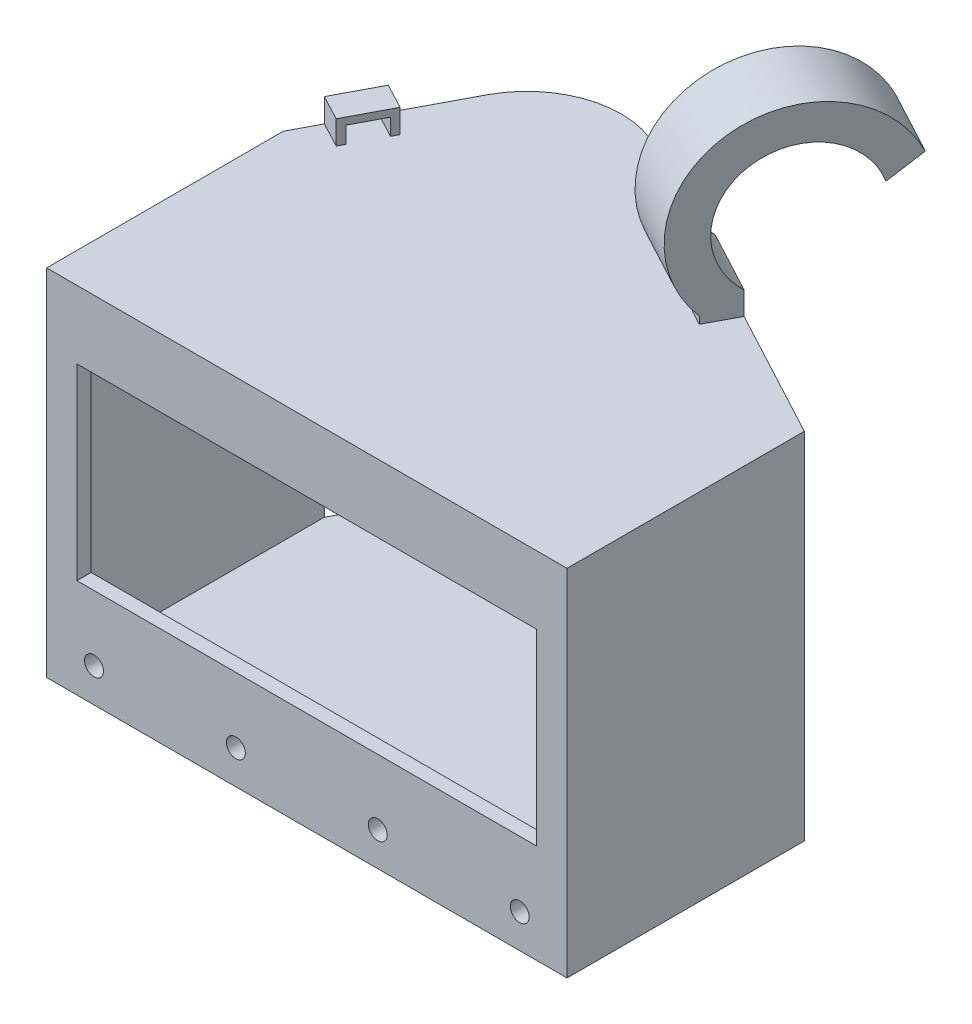
SolidWorks part; units mm, degrees
ref_plane "Plano frontal" through (0, 0, 0) normal (0, 0, 1) x (1, 0, 0)
ref_plane "Plano superior" through (0, 0, 0) normal (0, 1, 0) x (1, 0, 0)
ref_plane "Plano direito" through (0, 0, 0) normal (1, 0, 0) x (0, 0, -1)
sketch "Esboço1" plane through (0, 0, 0) normal (0, 1, 0) x (1, 0, 0)
  line L0 (-61.5267, 22.2983) -> (-61.5267, -27.7017)
  line L1 (-61.5267, -27.7017) -> (48.4733, -27.7017)
  line L2 (48.4733, -27.7017) -> (48.4733, 22.4627)
  line L3 (48.4733, 22.4627) -> (-19.533, 58.851)
  line L4 (-46.667, 50.5316) -> (-61.5267, 22.2983)
  line L5 (-61.5267, 22.2983) -> (48.4733, 22.4627) construction
  arc A0 (-19.533, 58.851) -> (-46.667, 50.5316) centre (-28.9687, 41.2167) ccw
  dimension "D1" = 20
  dimension "D2" = 62.156
  dimension "D3" = 28.236
extrude "Ressalto-extrusão4" add sketch "Esboço1" along normal blind 75
shell "Casca4" thickness 3
sketch "Esboço13" plane through (0, 0, 27.7017) normal (0, 0, 1) x (1, 0, 0)
  line L1 (-55.1131, 60.6291) -> (42.0597, 60.6291)
  line L2 (-55.1131, 60.6291) -> (-55.1131, 20.943)
  line L9 (-55.1131, 20.943) -> (42.0597, 20.943)
  line L10 (42.0597, 20.943) -> (42.0597, 60.6291)
  line L22 (48.4733, 75) -> (48.4733, 0) construction
  line L23 (-61.5267, 75) -> (-61.5267, 0) construction
  circle A0 centre (8.4733, 7.1439) radius 2
  circle A2 centre (38.4733, 7.1439) radius 2
  circle A3 centre (-51.5267, 7.1439) radius 2
  circle A4 centre (-21.5267, 7.1439) radius 2
  dimension "D2" = 2
extrude "Corte-extrusão2" cut sketch "Esboço13" against normal blind 75
sketch "Esboço20" plane through (0, 75, 0) normal (0, 1, 0) x (1, 0, 0)
  line L0 (-46.667, 50.5316) -> (-61.5267, 22.2983) construction
  line L3 (-48.5597, 34.053) -> (-53.8692, 36.8475)
  line L4 (-53.8692, 36.8475) -> (-58.5267, 27.9983)
  line L5 (-58.5267, 27.9983) -> (-53.2172, 25.2038)
  line L6 (-53.2172, 25.2038) -> (-48.5597, 34.053)
extrude "Ressalto-extrusão7" add sketch "Esboço20" along normal blind 5
sketch "Esboço21" plane through (-52.061, 0, -27.4005) normal (0.8849, 0, 0.4657) x (0.4657, 0, -0.8849)
  line L1 (-2.4824, 75) -> (7.5176, 75) construction
  line L2 (-0.9824, 75) -> (-0.9824, 78.5)
  line L3 (-0.9824, 78.5) -> (6.0176, 78.5)
  line L4 (6.0176, 78.5) -> (6.0176, 75)
  line L5 (-1.9375, 75) -> (42.4539, 75) construction
  line L6 (6.0176, 75) -> (-0.9824, 75)
extrude "Corte-extrusão7" cut sketch "Esboço21" against normal blind 15
sketch "Esboço23" plane through (0, 75, 0) normal (0, 1, 0) x (1, 0, 0)
  line L0 (-19.533, 58.851) -> (7.8573, 44.1952)
  line L1 (21.083, 37.1185) -> (48.4733, 22.4627)
  line L4 (21.083, 37.1185) -> (7.8573, 44.1952)
  line L5 (7.8573, 44.1952) -> (4.5548, 38.0232)
  line L6 (4.5548, 38.0232) -> (17.7805, 30.9465)
  line L7 (48.4733, 22.4627) -> (-19.533, 58.851) construction
  line L8 (17.7805, 30.9465) -> (21.083, 37.1185)
  line L9 (21.083, 37.1185) -> (34.34, 61.8947)
  line L10 (34.34, 61.8947) -> (21.1143, 68.9714)
  line L11 (21.1143, 68.9714) -> (7.8573, 44.1952)
  line L12 (27.7272, 65.4331) -> (14.4701, 40.6569)
  line L13 (21.083, 37.1185) -> (7.8573, 44.1952)
  line L14 (7.8573, 44.1952) -> (21.083, 37.1185)
  line L19 (17.7805, 30.9465) -> (21.083, 37.1185)
  line L20 (17.7805, 30.9465) -> (4.5548, 38.0232)
  line L21 (7.8573, 44.1952) -> (4.5548, 38.0232)
  line M6 (48.4733, 22.4627) -> (-19.533, 58.851)
extrude "Ressalto-extrusão9" add sketch "Esboço23" along normal blind 1.5 contours L6 L8 L4 L5 M6
sketch "Esboço27" plane through (0.9499, 0, 0.5083) normal (0.8817, 0, 0.4718) x (0.4718, 0, -0.8817)
  line L0 (42.6745, 76.5) -> (42.6745, 79.8599)
  line L1 (64.8399, 95.2109) -> (70.9836, 99.4658)
  line L2 (35.6745, 76.5) -> (42.6745, 76.5)
  arc A0 (64.8399, 95.2109) -> (42.6745, 79.8599) centre (51.5039, 90.789) ccw
  arc A1 (70.9836, 99.4658) -> (35.6745, 76.5) centre (51.5039, 90.789) ccw
extrude "Ressalto-extrusão10" add sketch "Esboço27" against normal blind 15
sketch "Esboço28" plane through (20.1331, 0, -37.6268) normal (0.4718, 0, -0.8817) x (-0.8817, 0, -0.4718)
  line L0 (2.3097, 75) -> (2.3097, 77.5)
  line L1 (6.0597, 75) -> (9.8097, 75)
  line L2 (6.0597, 75) -> (2.3097, 75)
  line L3 (2.3097, 77.5) -> (9.8097, 77.5)
  line L4 (9.8097, 77.5) -> (9.8097, 75)
extrude "Corte-extrusão8" cut sketch "Esboço28" against normal blind 9
